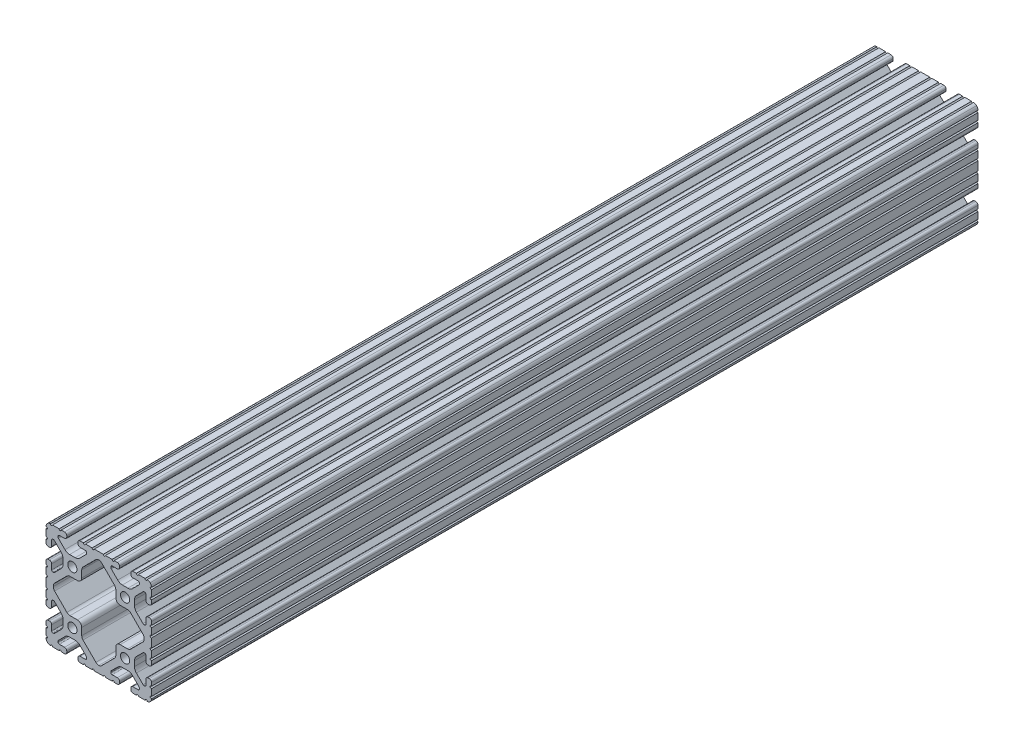
SolidWorks part; units mm, degrees
ref_plane "Front" through (0, 0, 0) normal (0, 0, 1) x (1, 0, 0)
ref_plane "Top" through (0, 0, 0) normal (0, 1, 0) x (1, 0, 0)
ref_plane "Right" through (0, 0, 0) normal (1, 0, 0) x (0, 0, -1)
sketch "Sketch1" plane through (0, 0, 0) normal (0, 0, 1) x (1, 0, 0)
  line L32 (-11.3637, -22.8433) -> (-2.0515, -32.1555)
  line L33 (-12.2936, -15.4686) -> (-12.2936, -20.5983)
  line L34 (-20.769, -12.2936) -> (-15.4686, -12.2936)
  line L35 (-31.9021, -2.4756) -> (-23.0141, -11.3637)
  line L36 (-23.0141, 11.3637) -> (-31.9021, 2.4756)
  line L37 (-15.4686, 12.2936) -> (-20.769, 12.2936)
  line L38 (-12.2936, 20.5983) -> (-12.2936, 15.4686)
  line L39 (-2.0515, 32.1555) -> (-11.3637, 22.8433)
  line L40 (11.3637, 22.8433) -> (2.0515, 32.1555)
  line L41 (12.2936, 15.4686) -> (12.2936, 20.5983)
  line L42 (20.769, 12.2936) -> (15.4686, 12.2936)
  line L43 (31.9021, 2.4756) -> (23.0141, 11.3637)
  line L44 (23.0141, -11.3637) -> (31.9021, -2.4756)
  line L45 (15.4686, -12.2936) -> (20.769, -12.2936)
  line L46 (12.2936, -20.5983) -> (12.2936, -15.4686)
  line L47 (2.0515, -32.1555) -> (11.3637, -22.8433)
  line L216 (-4.7773, 38.1) -> (-9.6053, 38.1)
  line L217 (-11.1289, 38.1) -> (-13.4112, 38.1)
  line L218 (-14.986, 36.5252) -> (-14.986, 35.6108)
  line L219 (-13.4112, 34.036) -> (-9.652, 34.036)
  line L220 (-8.763, 33.147) -> (-8.763, 32.4935)
  line L221 (-9.0234, 31.8649) -> (-13.6907, 27.1976)
  line L222 (-17.0493, 25.8064) -> (-21.0507, 25.8064)
  line L223 (-24.4093, 27.1976) -> (-29.1002, 31.8885)
  line L224 (-29.337, 32.7207) -> (-29.337, 33.147)
  line L225 (-28.448, 34.036) -> (-24.6888, 34.036)
  line L226 (-23.114, 35.6108) -> (-23.114, 36.5252)
  line L227 (-24.6888, 38.1) -> (-27.0772, 38.1)
  line L228 (-28.6011, 38.1) -> (-33.4288, 38.1)
  line L229 (-38.1, 33.373) -> (-38.1, 28.5453)
  line L230 (-38.1, 27.0238) -> (-38.1, 24.6302)
  line L231 (-36.5252, 23.0554) -> (-35.6108, 23.0554)
  line L232 (-34.036, 24.6302) -> (-34.036, 28.448)
  line L233 (-33.147, 29.337) -> (-32.6643, 29.337)
  line L234 (-32.0357, 29.0766) -> (-27.1976, 24.2385)
  line L235 (-25.8064, 20.8799) -> (-25.8064, 17.2201)
  line L236 (-27.1976, 13.8615) -> (-31.9489, 9.1101)
  line L237 (-32.7869, 8.763) -> (-33.0603, 8.763)
  line L238 (-34.036, 9.7387) -> (-34.036, 13.4698)
  line L239 (-35.6108, 15.0446) -> (-36.5252, 15.0446)
  line L240 (-38.1, 13.4698) -> (-38.1, 11.075)
  line L241 (-38.1, 9.552) -> (-38.1, 4.7238)
  line L242 (-38.1, 3.2007) -> (-38.1, -3.2007)
  line L243 (-38.1, -4.7238) -> (-38.1, -9.552)
  line L244 (-38.1, -11.075) -> (-38.1, -13.4698)
  line L245 (-36.5252, -15.0446) -> (-35.6108, -15.0446)
  line L246 (-34.036, -13.4698) -> (-34.036, -9.7387)
  line L247 (-33.0603, -8.763) -> (-32.7869, -8.763)
  line L248 (-31.9489, -9.1101) -> (-27.1976, -13.8615)
  line L249 (-25.8064, -17.2201) -> (-25.8064, -20.8799)
  line L250 (-27.1976, -24.2385) -> (-32.0357, -29.0766)
  line L251 (-32.6643, -29.337) -> (-33.147, -29.337)
  line L252 (-34.036, -28.448) -> (-34.036, -24.6302)
  line L253 (-35.6108, -23.0554) -> (-36.5252, -23.0554)
  line L254 (-38.1, -24.6302) -> (-38.1, -27.0238)
  line L255 (-38.1, -28.5453) -> (-38.1, -33.373)
  line L256 (-33.4288, -38.1) -> (-28.6011, -38.1)
  line L257 (-27.0772, -38.1) -> (-24.6888, -38.1)
  line L258 (-23.114, -36.5252) -> (-23.114, -35.6108)
  line L259 (-24.6888, -34.036) -> (-28.448, -34.036)
  line L260 (-29.337, -33.147) -> (-29.337, -32.7207)
  line L261 (-29.1002, -31.8885) -> (-24.4093, -27.1976)
  line L262 (-21.0507, -25.8064) -> (-17.0493, -25.8064)
  line L263 (-13.6907, -27.1976) -> (-9.0234, -31.8649)
  line L264 (-8.763, -32.4935) -> (-8.763, -33.147)
  line L265 (-9.652, -34.036) -> (-13.4112, -34.036)
  line L266 (-14.986, -35.6108) -> (-14.986, -36.5252)
  line L267 (-13.4112, -38.1) -> (-11.1289, -38.1)
  line L268 (-9.6053, -38.1) -> (-4.7773, -38.1)
  line L269 (-3.2537, -38.1) -> (3.2537, -38.1)
  line L270 (4.7773, -38.1) -> (9.6053, -38.1)
  line L271 (11.1289, -38.1) -> (13.4112, -38.1)
  line L272 (14.986, -36.5252) -> (14.986, -35.6108)
  line L273 (13.4112, -34.036) -> (9.652, -34.036)
  line L274 (8.763, -33.147) -> (8.763, -32.4935)
  line L275 (9.0234, -31.8649) -> (13.6907, -27.1976)
  line L276 (17.0493, -25.8064) -> (21.0507, -25.8064)
  line L277 (24.4093, -27.1976) -> (29.1002, -31.8885)
  line L278 (29.337, -32.7207) -> (29.337, -33.147)
  line L279 (28.448, -34.036) -> (24.6888, -34.036)
  line L280 (23.114, -35.6108) -> (23.114, -36.5252)
  line L281 (24.6888, -38.1) -> (27.0772, -38.1)
  line L282 (28.6011, -38.1) -> (33.4288, -38.1)
  line L283 (38.1, -33.373) -> (38.1, -28.5453)
  line L284 (38.1, -27.0238) -> (38.1, -24.6302)
  line L285 (36.5252, -23.0554) -> (35.6108, -23.0554)
  line L286 (34.036, -24.6302) -> (34.036, -28.448)
  line L287 (33.147, -29.337) -> (32.6643, -29.337)
  line L288 (32.0357, -29.0766) -> (27.1976, -24.2385)
  line L289 (25.8064, -20.8799) -> (25.8064, -17.2201)
  line L290 (27.1976, -13.8615) -> (31.9489, -9.1101)
  line L291 (32.7869, -8.763) -> (33.0603, -8.763)
  line L292 (34.036, -9.7387) -> (34.036, -13.4698)
  line L293 (35.6108, -15.0446) -> (36.5252, -15.0446)
  line L294 (38.1, -13.4698) -> (38.1, -11.075)
  line L295 (38.1, -9.552) -> (38.1, -4.7238)
  line L296 (38.1, -3.2007) -> (38.1, 3.2007)
  line L297 (38.1, 4.7238) -> (38.1, 9.552)
  line L298 (38.1, 11.075) -> (38.1, 13.4698)
  line L299 (36.5252, 15.0446) -> (35.6108, 15.0446)
  line L300 (34.036, 13.4698) -> (34.036, 9.7387)
  line L301 (33.0603, 8.763) -> (32.7869, 8.763)
  line L302 (31.9489, 9.1101) -> (27.1976, 13.8615)
  line L303 (25.8064, 17.2201) -> (25.8064, 20.8799)
  line L304 (27.1976, 24.2385) -> (32.0357, 29.0766)
  line L305 (32.6643, 29.337) -> (33.147, 29.337)
  line L306 (34.036, 28.448) -> (34.036, 24.6302)
  line L307 (35.6108, 23.0554) -> (36.5252, 23.0554)
  line L308 (38.1, 24.6302) -> (38.1, 27.0238)
  line L309 (38.1, 28.5453) -> (38.1, 33.373)
  line L310 (33.4288, 38.1) -> (28.6011, 38.1)
  line L311 (27.0772, 38.1) -> (24.6888, 38.1)
  line L312 (23.114, 36.5252) -> (23.114, 35.6108)
  line L313 (24.6888, 34.036) -> (28.448, 34.036)
  line L314 (29.337, 33.147) -> (29.337, 32.7207)
  line L315 (29.1002, 31.8885) -> (24.4093, 27.1976)
  line L316 (21.0507, 25.8064) -> (17.0493, 25.8064)
  line L317 (13.6907, 27.1976) -> (9.0234, 31.8649)
  line L318 (8.763, 32.4935) -> (8.763, 33.147)
  line L319 (9.652, 34.036) -> (13.4112, 34.036)
  line L320 (14.986, 35.6108) -> (14.986, 36.5252)
  line L321 (13.4112, 38.1) -> (11.1289, 38.1)
  line L322 (9.6053, 38.1) -> (4.7773, 38.1)
  line L323 (3.2537, 38.1) -> (-3.2537, 38.1)
  circle A2 centre (-19.05, 19.05) radius 3.3274
  circle A4 centre (-19.05, -19.05) radius 3.3274
  circle A6 centre (19.05, -19.05) radius 3.3274
  circle A8 centre (19.05, 19.05) radius 3.3274
  arc A42 (0, -33.011) -> (2.0515, -32.1555) centre (-0.0139, -30.09) ccw
  arc A43 (-2.0515, -32.1555) -> (0, -33.011) centre (0.0139, -30.09) ccw
  arc A44 (-12.2936, -20.5983) -> (-11.3637, -22.8433) centre (-9.1186, -20.5983) ccw
  arc A45 (-12.2936, -15.4686) -> (-15.4686, -12.2936) centre (-15.4686, -15.4686) ccw
  arc A46 (-23.0141, -11.3637) -> (-20.769, -12.2936) centre (-20.769, -9.1186) ccw
  arc A47 (-32.7287, 0) -> (-31.9021, -2.4756) centre (-29.8367, -0.4102) ccw
  arc A48 (-31.9021, 2.4756) -> (-32.7287, 0) centre (-29.8367, 0.4102) ccw
  arc A49 (-20.769, 12.2936) -> (-23.0141, 11.3637) centre (-20.769, 9.1186) ccw
  arc A50 (-15.4686, 12.2936) -> (-12.2936, 15.4686) centre (-15.4686, 15.4686) ccw
  arc A51 (-11.3637, 22.8433) -> (-12.2936, 20.5983) centre (-9.1186, 20.5983) ccw
  arc A52 (0, 33.011) -> (-2.0515, 32.1555) centre (0.0139, 30.09) ccw
  arc A53 (2.0515, 32.1555) -> (0, 33.011) centre (-0.0139, 30.09) ccw
  arc A54 (12.2936, 20.5983) -> (11.3637, 22.8433) centre (9.1186, 20.5983) ccw
  arc A55 (12.2936, 15.4686) -> (15.4686, 12.2936) centre (15.4686, 15.4686) ccw
  arc A56 (23.0141, 11.3637) -> (20.769, 12.2936) centre (20.769, 9.1186) ccw
  arc A57 (32.7287, 0) -> (31.9021, 2.4756) centre (29.8367, 0.4102) ccw
  arc A58 (31.9021, -2.4756) -> (32.7287, 0) centre (29.8367, -0.4102) ccw
  arc A59 (20.769, -12.2936) -> (23.0141, -11.3637) centre (20.769, -9.1186) ccw
  arc A60 (15.4686, -12.2936) -> (12.2936, -15.4686) centre (15.4686, -15.4686) ccw
  arc A61 (11.3637, -22.8433) -> (12.2936, -20.5983) centre (9.1186, -20.5983) ccw
  arc A240 (-4.7773, 38.1) -> (-3.2537, 38.1) centre (-4.0155, 38.0824) ccw
  arc A241 (-11.1289, 38.1) -> (-9.6053, 38.1) centre (-10.3671, 38.0824) ccw
  arc A242 (-13.4112, 38.1) -> (-14.986, 36.5252) centre (-13.4112, 36.5252) ccw
  arc A243 (-14.986, 35.6108) -> (-13.4112, 34.036) centre (-13.4112, 35.6108) ccw
  arc A244 (-8.763, 33.147) -> (-9.652, 34.036) centre (-9.652, 33.147) ccw
  arc A245 (-9.0234, 31.8649) -> (-8.763, 32.4935) centre (-9.652, 32.4935) ccw
  arc A246 (-17.0493, 25.8064) -> (-13.6907, 27.1976) centre (-17.0493, 30.5562) ccw
  arc A247 (-24.4093, 27.1976) -> (-21.0507, 25.8064) centre (-21.0507, 30.5562) ccw
  arc A248 (-29.337, 32.7207) -> (-29.1002, 31.8885) centre (-28.4716, 32.5172) ccw
  arc A249 (-28.448, 34.036) -> (-29.337, 33.147) centre (-28.448, 33.147) ccw
  arc A250 (-24.6888, 34.036) -> (-23.114, 35.6108) centre (-24.6888, 35.6108) ccw
  arc A251 (-23.114, 36.5252) -> (-24.6888, 38.1) centre (-24.6888, 36.5252) ccw
  arc A252 (-28.6011, 38.1) -> (-27.0772, 38.1) centre (-27.8392, 38.0824) ccw
  arc A253 (-34.9527, 38.1) -> (-33.4288, 38.1) centre (-34.1907, 38.0824) ccw
  arc A254 (-34.9527, 38.1) -> (-37.0861, 37.1826) centre (-34.8521, 34.9266) ccw
  arc A255 (-37.0861, 37.1826) -> (-38.1, 34.8455) centre (-34.925, 34.8566) ccw
  arc A256 (-38.1, 33.373) -> (-38.1, 34.8455) centre (-37.9035, 34.1092) ccw
  arc A257 (-38.1, 27.0238) -> (-38.1, 28.5453) centre (-37.9035, 27.7845) ccw
  arc A258 (-38.1, 24.6302) -> (-36.5252, 23.0554) centre (-36.5252, 24.6302) ccw
  arc A259 (-35.6108, 23.0554) -> (-34.036, 24.6302) centre (-35.6108, 24.6302) ccw
  arc A260 (-33.147, 29.337) -> (-34.036, 28.448) centre (-33.147, 28.448) ccw
  arc A261 (-32.0357, 29.0766) -> (-32.6643, 29.337) centre (-32.6643, 28.448) ccw
  arc A262 (-25.8064, 20.8799) -> (-27.1976, 24.2385) centre (-30.5562, 20.8799) ccw
  arc A263 (-27.1976, 13.8615) -> (-25.8064, 17.2201) centre (-30.5562, 17.2201) ccw
  arc A264 (-32.7869, 8.763) -> (-31.9489, 9.1101) centre (-32.7869, 9.9481) ccw
  arc A265 (-34.036, 9.7387) -> (-33.0603, 8.763) centre (-33.0603, 9.7387) ccw
  arc A266 (-34.036, 13.4698) -> (-35.6108, 15.0446) centre (-35.6108, 13.4698) ccw
  arc A267 (-36.5252, 15.0446) -> (-38.1, 13.4698) centre (-36.5252, 13.4698) ccw
  arc A268 (-38.1, 9.552) -> (-38.1, 11.075) centre (-37.9035, 10.3135) ccw
  arc A269 (-38.1, 3.2007) -> (-38.1, 4.7238) centre (-37.9035, 3.9622) ccw
  arc A270 (-38.1, -4.7238) -> (-38.1, -3.2007) centre (-37.9035, -3.9622) ccw
  arc A271 (-38.1, -11.075) -> (-38.1, -9.552) centre (-37.9035, -10.3135) ccw
  arc A272 (-38.1, -13.4698) -> (-36.5252, -15.0446) centre (-36.5252, -13.4698) ccw
  arc A273 (-35.6108, -15.0446) -> (-34.036, -13.4698) centre (-35.6108, -13.4698) ccw
  arc A274 (-33.0603, -8.763) -> (-34.036, -9.7387) centre (-33.0603, -9.7387) ccw
  arc A275 (-31.9489, -9.1101) -> (-32.7869, -8.763) centre (-32.7869, -9.9481) ccw
  arc A276 (-25.8064, -17.2201) -> (-27.1976, -13.8615) centre (-30.5562, -17.2201) ccw
  arc A277 (-27.1976, -24.2385) -> (-25.8064, -20.8799) centre (-30.5562, -20.8799) ccw
  arc A278 (-32.6643, -29.337) -> (-32.0357, -29.0766) centre (-32.6643, -28.448) ccw
  arc A279 (-34.036, -28.448) -> (-33.147, -29.337) centre (-33.147, -28.448) ccw
  arc A280 (-34.036, -24.6302) -> (-35.6108, -23.0554) centre (-35.6108, -24.6302) ccw
  arc A281 (-36.5252, -23.0554) -> (-38.1, -24.6302) centre (-36.5252, -24.6302) ccw
  arc A282 (-38.1, -28.5453) -> (-38.1, -27.0238) centre (-37.9035, -27.7845) ccw
  arc A283 (-38.1, -34.8455) -> (-38.1, -33.373) centre (-37.9035, -34.1092) ccw
  arc A284 (-38.1, -34.8455) -> (-37.0861, -37.1826) centre (-34.925, -34.8566) ccw
  arc A285 (-37.0861, -37.1826) -> (-34.9527, -38.1) centre (-34.8521, -34.9266) ccw
  arc A286 (-33.4288, -38.1) -> (-34.9527, -38.1) centre (-34.1907, -38.0824) ccw
  arc A287 (-27.0772, -38.1) -> (-28.6011, -38.1) centre (-27.8392, -38.0824) ccw
  arc A288 (-24.6888, -38.1) -> (-23.114, -36.5252) centre (-24.6888, -36.5252) ccw
  arc A289 (-23.114, -35.6108) -> (-24.6888, -34.036) centre (-24.6888, -35.6108) ccw
  arc A290 (-29.337, -33.147) -> (-28.448, -34.036) centre (-28.448, -33.147) ccw
  arc A291 (-29.1002, -31.8885) -> (-29.337, -32.7207) centre (-28.4716, -32.5172) ccw
  arc A292 (-21.0507, -25.8064) -> (-24.4093, -27.1976) centre (-21.0507, -30.5562) ccw
  arc A293 (-13.6907, -27.1976) -> (-17.0493, -25.8064) centre (-17.0493, -30.5562) ccw
  arc A294 (-8.763, -32.4935) -> (-9.0234, -31.8649) centre (-9.652, -32.4935) ccw
  arc A295 (-9.652, -34.036) -> (-8.763, -33.147) centre (-9.652, -33.147) ccw
  arc A296 (-13.4112, -34.036) -> (-14.986, -35.6108) centre (-13.4112, -35.6108) ccw
  arc A297 (-14.986, -36.5252) -> (-13.4112, -38.1) centre (-13.4112, -36.5252) ccw
  arc A298 (-9.6053, -38.1) -> (-11.1289, -38.1) centre (-10.3671, -38.0824) ccw
  arc A299 (-3.2537, -38.1) -> (-4.7773, -38.1) centre (-4.0155, -38.0824) ccw
  arc A300 (4.7773, -38.1) -> (3.2537, -38.1) centre (4.0155, -38.0824) ccw
  arc A301 (11.1289, -38.1) -> (9.6053, -38.1) centre (10.3671, -38.0824) ccw
  arc A302 (13.4112, -38.1) -> (14.986, -36.5252) centre (13.4112, -36.5252) ccw
  arc A303 (14.986, -35.6108) -> (13.4112, -34.036) centre (13.4112, -35.6108) ccw
  arc A304 (8.763, -33.147) -> (9.652, -34.036) centre (9.652, -33.147) ccw
  arc A305 (9.0234, -31.8649) -> (8.763, -32.4935) centre (9.652, -32.4935) ccw
  arc A306 (17.0493, -25.8064) -> (13.6907, -27.1976) centre (17.0493, -30.5562) ccw
  arc A307 (24.4093, -27.1976) -> (21.0507, -25.8064) centre (21.0507, -30.5562) ccw
  arc A308 (29.337, -32.7207) -> (29.1002, -31.8885) centre (28.4716, -32.5172) ccw
  arc A309 (28.448, -34.036) -> (29.337, -33.147) centre (28.448, -33.147) ccw
  arc A310 (24.6888, -34.036) -> (23.114, -35.6108) centre (24.6888, -35.6108) ccw
  arc A311 (23.114, -36.5252) -> (24.6888, -38.1) centre (24.6888, -36.5252) ccw
  arc A312 (28.6011, -38.1) -> (27.0772, -38.1) centre (27.8392, -38.0824) ccw
  arc A313 (34.9527, -38.1) -> (33.4288, -38.1) centre (34.1907, -38.0824) ccw
  arc A314 (34.9527, -38.1) -> (37.0861, -37.1826) centre (34.8521, -34.9266) ccw
  arc A315 (37.0861, -37.1826) -> (38.1, -34.8455) centre (34.925, -34.8566) ccw
  arc A316 (38.1, -33.373) -> (38.1, -34.8455) centre (37.9035, -34.1092) ccw
  arc A317 (38.1, -27.0238) -> (38.1, -28.5453) centre (37.9035, -27.7845) ccw
  arc A318 (38.1, -24.6302) -> (36.5252, -23.0554) centre (36.5252, -24.6302) ccw
  arc A319 (35.6108, -23.0554) -> (34.036, -24.6302) centre (35.6108, -24.6302) ccw
  arc A320 (33.147, -29.337) -> (34.036, -28.448) centre (33.147, -28.448) ccw
  arc A321 (32.0357, -29.0766) -> (32.6643, -29.337) centre (32.6643, -28.448) ccw
  arc A322 (25.8064, -20.8799) -> (27.1976, -24.2385) centre (30.5562, -20.8799) ccw
  arc A323 (27.1976, -13.8615) -> (25.8064, -17.2201) centre (30.5562, -17.2201) ccw
  arc A324 (32.7869, -8.763) -> (31.9489, -9.1101) centre (32.7869, -9.9481) ccw
  arc A325 (34.036, -9.7387) -> (33.0603, -8.763) centre (33.0603, -9.7387) ccw
  arc A326 (34.036, -13.4698) -> (35.6108, -15.0446) centre (35.6108, -13.4698) ccw
  arc A327 (36.5252, -15.0446) -> (38.1, -13.4698) centre (36.5252, -13.4698) ccw
  arc A328 (38.1, -9.552) -> (38.1, -11.075) centre (37.9035, -10.3135) ccw
  arc A329 (38.1, -3.2007) -> (38.1, -4.7238) centre (37.9035, -3.9622) ccw
  arc A330 (38.1, 4.7238) -> (38.1, 3.2007) centre (37.9035, 3.9622) ccw
  arc A331 (38.1, 11.075) -> (38.1, 9.552) centre (37.9035, 10.3135) ccw
  arc A332 (38.1, 13.4698) -> (36.5252, 15.0446) centre (36.5252, 13.4698) ccw
  arc A333 (35.6108, 15.0446) -> (34.036, 13.4698) centre (35.6108, 13.4698) ccw
  arc A334 (33.0603, 8.763) -> (34.036, 9.7387) centre (33.0603, 9.7387) ccw
  arc A335 (31.9489, 9.1101) -> (32.7869, 8.763) centre (32.7869, 9.9481) ccw
  arc A336 (25.8064, 17.2201) -> (27.1976, 13.8615) centre (30.5562, 17.2201) ccw
  arc A337 (27.1976, 24.2385) -> (25.8064, 20.8799) centre (30.5562, 20.8799) ccw
  arc A338 (32.6643, 29.337) -> (32.0357, 29.0766) centre (32.6643, 28.448) ccw
  arc A339 (34.036, 28.448) -> (33.147, 29.337) centre (33.147, 28.448) ccw
  arc A340 (34.036, 24.6302) -> (35.6108, 23.0554) centre (35.6108, 24.6302) ccw
  arc A341 (36.5252, 23.0554) -> (38.1, 24.6302) centre (36.5252, 24.6302) ccw
  arc A342 (38.1, 28.5453) -> (38.1, 27.0238) centre (37.9035, 27.7845) ccw
  arc A343 (38.1, 34.8455) -> (38.1, 33.373) centre (37.9035, 34.1092) ccw
  arc A344 (38.1, 34.8455) -> (37.0861, 37.1826) centre (34.925, 34.8566) ccw
  arc A345 (37.0861, 37.1826) -> (34.9527, 38.1) centre (34.8521, 34.9266) ccw
  arc A346 (33.4288, 38.1) -> (34.9527, 38.1) centre (34.1907, 38.0824) ccw
  arc A347 (27.0772, 38.1) -> (28.6011, 38.1) centre (27.8392, 38.0824) ccw
  arc A348 (24.6888, 38.1) -> (23.114, 36.5252) centre (24.6888, 36.5252) ccw
  arc A349 (23.114, 35.6108) -> (24.6888, 34.036) centre (24.6888, 35.6108) ccw
  arc A350 (29.337, 33.147) -> (28.448, 34.036) centre (28.448, 33.147) ccw
  arc A351 (29.1002, 31.8885) -> (29.337, 32.7207) centre (28.4716, 32.5172) ccw
  arc A352 (21.0507, 25.8064) -> (24.4093, 27.1976) centre (21.0507, 30.5562) ccw
  arc A353 (13.6907, 27.1976) -> (17.0493, 25.8064) centre (17.0493, 30.5562) ccw
  arc A354 (8.763, 32.4935) -> (9.0234, 31.8649) centre (9.652, 32.4935) ccw
  arc A355 (9.652, 34.036) -> (8.763, 33.147) centre (9.652, 33.147) ccw
  arc A356 (13.4112, 34.036) -> (14.986, 35.6108) centre (13.4112, 35.6108) ccw
  arc A357 (14.986, 36.5252) -> (13.4112, 38.1) centre (13.4112, 36.5252) ccw
  arc A358 (9.6053, 38.1) -> (11.1289, 38.1) centre (10.3671, 38.0824) ccw
  arc A359 (3.2537, 38.1) -> (4.7773, 38.1) centre (4.0155, 38.0824) ccw
extrude "Boss-Extrude1" add sketch "Sketch1" along normal mid plane 596.9
